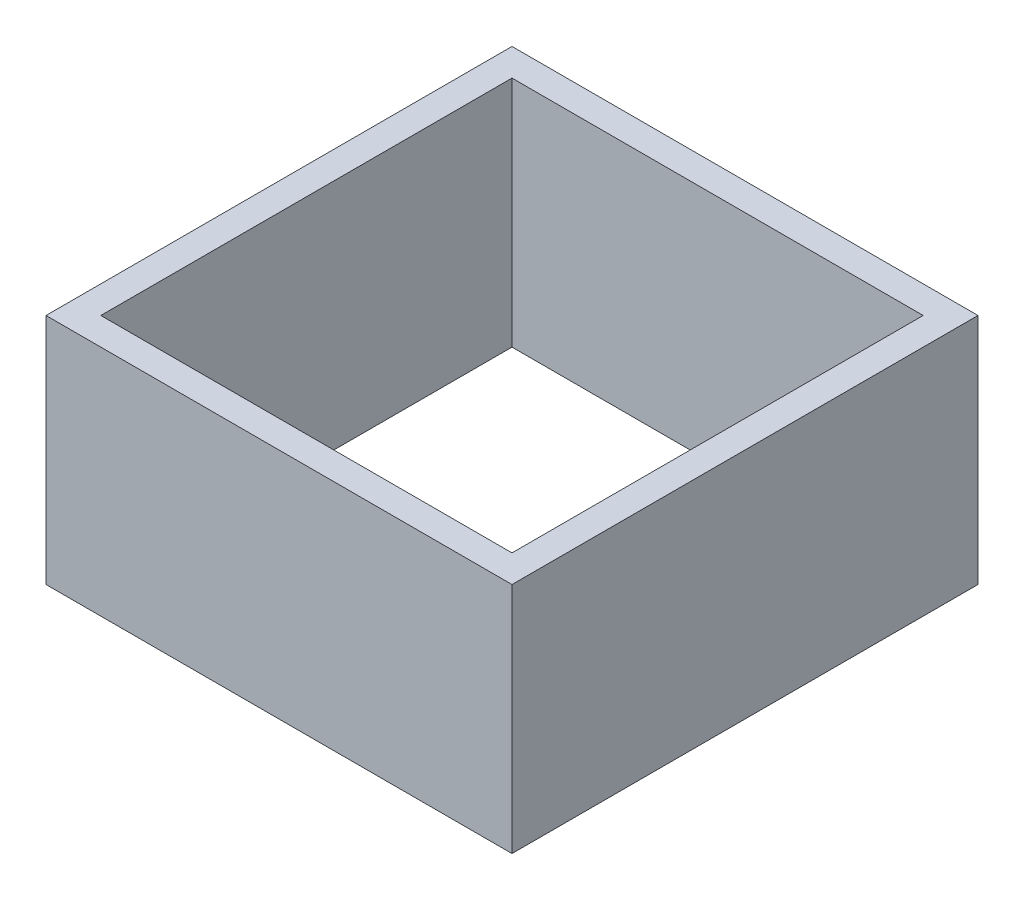
SolidWorks part; units mm, degrees
ref_plane "Front" through (0, 0, 0) normal (0, 0, 1) x (1, 0, 0)
ref_plane "Top" through (0, 0, 0) normal (0, 1, 0) x (1, 0, 0)
ref_plane "Right" through (0, 0, 0) normal (1, 0, 0) x (0, 0, -1)
sketch "Sketch1" plane through (0, 0, 0) normal (0, 1, 0) x (1, 0, 0)
  line L1 (-85, -85) -> (85, -85)
  line L2 (-85, -85) -> (-85, 85)
  line L3 (-85, 85) -> (85, 85)
  line L4 (85, -85) -> (85, 85)
  line L5 (-85, -85) -> (85, 85) construction
  line L6 (-85, 85) -> (85, -85) construction
  point P0 (0, 0)
extrude "Boss-Extrude1" add sketch "Sketch1" along normal blind 85
sketch "Sketch2" plane through (0, 85, 0) normal (0, 1, 0) x (1, 0, 0)
  line L1 (75, 75) -> (-75, 75)
  line L2 (75, 75) -> (75, -75)
  line L3 (75, -75) -> (-75, -75)
  line L4 (-75, 75) -> (-75, -75)
  line L5 (75, 75) -> (-75, -75) construction
  line L6 (75, -75) -> (-75, 75) construction
  point P0 (0, 0)
extrude "Cut-Extrude1" cut sketch "Sketch2" against normal blind 85
